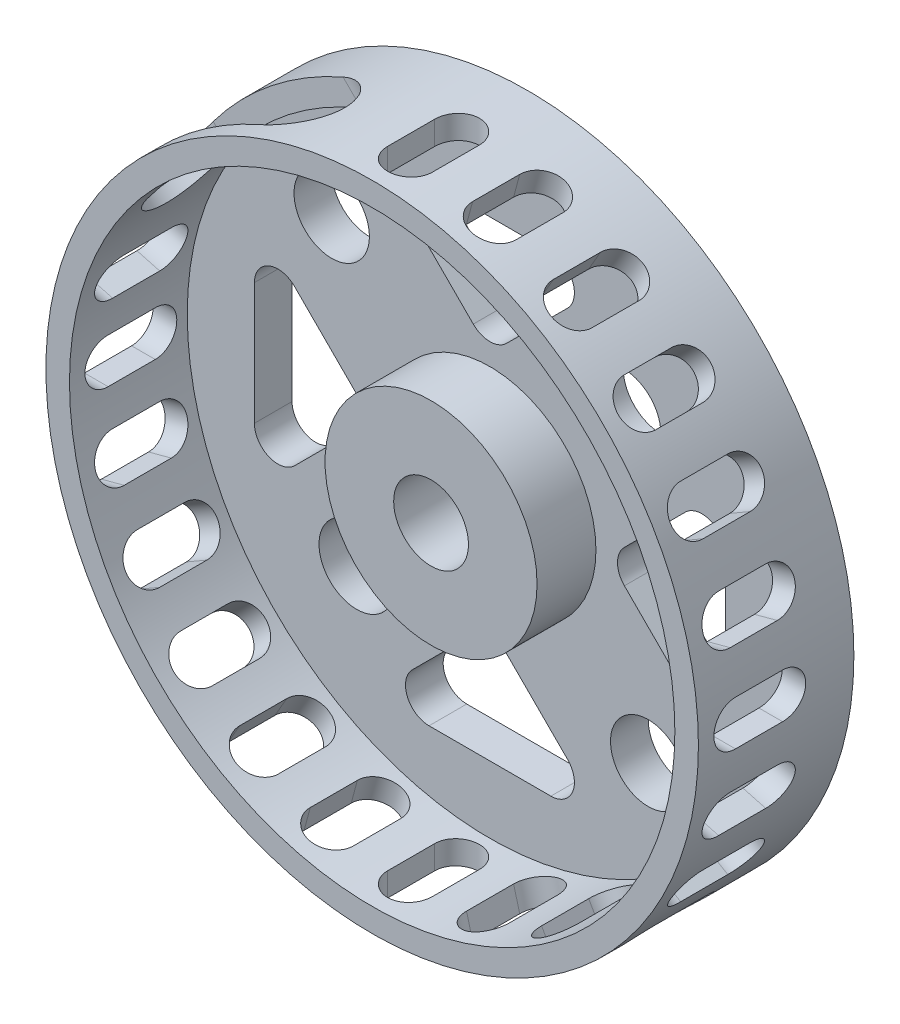
SolidWorks part; units mm, degrees
ref_plane "Front Plane" through (0, 0, 0) normal (0, 0, 1) x (1, 0, 0)
ref_plane "Top Plane" through (0, 0, 0) normal (0, 1, 0) x (1, 0, 0)
ref_plane "Right Plane" through (0, 0, 0) normal (1, 0, 0) x (0, 0, -1)
sketch "Sketch1" plane through (0, 0, 0) normal (0, 0, 1) x (1, 0, 0)
  circle A0 centre (0, 0) radius 13.85
  dimension "D1" = 27.7
extrude "Boss-Extrude1" add sketch "Sketch1" along normal blind 6.6
ref_plane "Plane2" through (0, 0, 6.6) normal (0, 0, 1) x (1, 0, 0)
sketch "Sketch3" plane through (0, 0, 6.6) normal (0, 0, 1) x (1, 0, 0)
  circle A0 centre (0, 0) radius 12.85
  dimension "D1" = 25.7
extrude "Cut-Extrude1" cut sketch "Sketch3" against normal blind 5
ref_plane "Plane3" through (0, 0, 1.6) normal (0, 0, 1) x (1, 0, 0)
sketch "Sketch4" plane through (0, 0, 1.6) normal (0, 0, 1) x (1, 0, 0)
  line L0 (0, 0) -> (-6.7175, 6.7175) construction
  line L1 (0, 0) -> (6.7175, -6.7175) construction
  line L2 (0, 0) -> (-5.6569, -5.6569) construction
  line L3 (0, 0) -> (5.6569, 5.6569) construction
  line L4 (0, 0) -> (0, 10) construction
  line L5 (0, 10) -> (2.5858, 10)
  line L7 (0, 10) -> (-2.5858, 10)
  line L9 (-3.2929, 8.2929) -> (-0.7071, 5.7071)
  line L11 (0.7071, 5.7071) -> (3.2929, 8.2929)
  line L12 (5.7071, -0.7071) -> (8.2929, -3.2929)
  line L13 (10, 0) -> (10, -2.5858)
  line L14 (10, 0) -> (10, 2.5858)
  line L15 (8.2929, 3.2929) -> (5.7071, 0.7071)
  line L16 (-0.7071, -5.7071) -> (-3.2929, -8.2929)
  line L17 (0, -10) -> (-2.5858, -10)
  line L18 (0, -10) -> (2.5858, -10)
  line L19 (3.2929, -8.2929) -> (0.7071, -5.7071)
  line L20 (-5.7071, 0.7071) -> (-8.2929, 3.2929)
  line L21 (-10, 0) -> (-10, 2.5858)
  line L22 (-10, 0) -> (-10, -2.5858)
  line L23 (-8.2929, -3.2929) -> (-5.7071, -0.7071)
  circle A0 centre (0, 0) radius 4.5
  circle A3 centre (-6.7175, 6.7175) radius 1.6
  circle A4 centre (5.6569, 5.6569) radius 1.6
  circle A5 centre (-5.6569, -5.6569) radius 1.6
  circle A6 centre (6.7175, -6.7175) radius 1.6
  arc A7 (0.7071, 5.7071) -> (-0.7071, 5.7071) centre (0, 6.4142) cw
  arc A8 (3.2929, 8.2929) -> (2.5858, 10) centre (2.5858, 9) ccw
  arc A9 (-3.2929, 8.2929) -> (-2.5858, 10) centre (-2.5858, 9) cw
  arc A10 (8.2929, -3.2929) -> (10, -2.5858) centre (9, -2.5858) ccw
  arc A11 (5.7071, -0.7071) -> (5.7071, 0.7071) centre (6.4142, 0) cw
  arc A12 (8.2929, 3.2929) -> (10, 2.5858) centre (9, 2.5858) cw
  arc A13 (-3.2929, -8.2929) -> (-2.5858, -10) centre (-2.5858, -9) ccw
  arc A14 (-0.7071, -5.7071) -> (0.7071, -5.7071) centre (0, -6.4142) cw
  arc A15 (3.2929, -8.2929) -> (2.5858, -10) centre (2.5858, -9) cw
  arc A16 (-8.2929, 3.2929) -> (-10, 2.5858) centre (-9, 2.5858) ccw
  arc A17 (-5.7071, 0.7071) -> (-5.7071, -0.7071) centre (-6.4142, 0) cw
  arc A18 (-8.2929, -3.2929) -> (-10, -2.5858) centre (-9, -2.5858) cw
  point P17 (0, 5)
  point P20 (5, 10)
  point P23 (-5, 10)
  point P57 (0, 0)
  dimension "D1" = 9
  dimension "D2" = 10
  dimension "D3" = 5
  dimension "D4" = 3.2
  dimension "D5" = 3.2
  dimension "D6" = 3.2
  dimension "D7" = 3.2
  dimension "D9" = 1
  dimension "D8" = 5
  dimension "D10" = 4
extrude "Cut-Extrude2" cut sketch "Sketch4" against normal blind 4.6
ref_plane "Plane4" through (0, 0, 1.6) normal (0, 0, 1) x (1, 0, 0)
sketch "Sketch5" plane through (0, 0, 1.6) normal (0, 0, 1) x (1, 0, 0)
  circle A0 centre (0, 0) radius 4.5
extrude "Boss-Extrude3" add sketch "Sketch5" along normal blind 2.5 and the other way blind 1.5
sketch "Sketch6" plane through (0, 0, 0.1) normal (0, 0, -1) x (-1, 0, 0)
  circle A0 centre (0, 0) radius 2.65
  dimension "D1" = 5.3
extrude "Boss-Extrude4" add sketch "Sketch6" along normal blind 0.5
sketch "Sketch7" plane through (0, 0, -0.4) normal (0, 0, -1) x (-1, 0, 0)
  circle A0 centre (0, 0) radius 1.5875
  dimension "D1" = 3.175
extrude "Cut-Extrude3" cut sketch "Sketch7" against normal through all
ref_plane "Plane5" through (0, 10, 0) normal (0, 1, 0) x (1, 0, 0)
sketch "Sketch10" plane through (0, 10, 0) normal (0, 1, 0) x (1, 0, 0)
  line L3 (0.95, -2.9943) -> (0.95, -4.9943)
  line L5 (-0.95, -2.9943) -> (-0.95, -4.9943)
  arc A0 (-0.95, -4.9943) -> (0.95, -4.9943) centre (0, -4.9943) ccw
  arc A2 (0.95, -2.9943) -> (-0.95, -2.9943) centre (0, -2.9943) ccw
  point P3 (0, -3.9943)
  dimension "D1" = 2
  dimension "D2" = 1.9
extrude "Cut-Extrude4" cut sketch "Sketch10" along normal through all
pattern_circular "CirPattern1" count 20 every 15 about axis through (0, 0, 0) along (0, 0, 1) of "Cut-Extrude4"
ref_plane "Plane6" through (-9.7934, 9.7934, 0) normal (-0.7071, 0.7071, 0) x (0, 0, -1)
sketch "Sketch11" plane through (-9.7934, 9.7934, 0) normal (-0.7071, 0.7071, 0) x (0, 0, -1)
  line L0 (-3.9943, -9.0986) -> (-3.9943, -6.7563) construction
  line L1 (-2.9943, -9.0986) -> (-4.9943, -9.0986) construction
  line L2 (-4.9943, 6.086) -> (-2.9943, 6.086) construction
  line L5 (-5.7443, -5.0063) -> (-5.7443, 1.9937)
  line L7 (-2.2443, -5.0063) -> (-2.2443, 1.9937)
  line L12 (-3.9943, 3.7437) -> (-3.9943, 6.086) construction
  arc A0 (-2.2443, 1.9937) -> (-5.7443, 1.9937) centre (-3.9943, 1.9937) ccw
  arc A1 (-5.7443, -5.0063) -> (-2.2443, -5.0063) centre (-3.9943, -5.0063) ccw
  point P6 (-3.9943, -1.5063)
  dimension "D1" = 7
  dimension "D2" = 3.5
extrude "Cut-Extrude5" cut sketch "Sketch11" against normal blind 5.1
